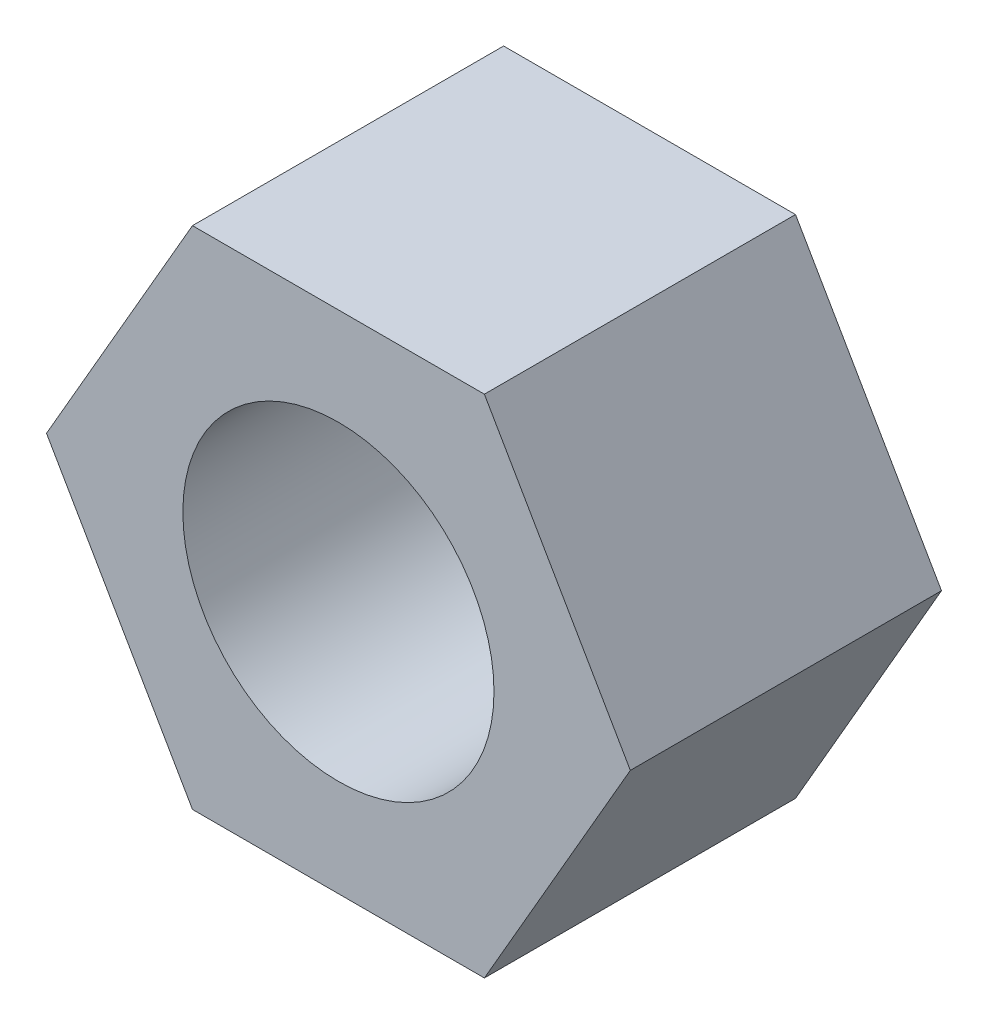
SolidWorks part; units mm, degrees
ref_plane "Front" through (0, 0, 0) normal (0, 0, 1) x (1, 0, 0)
ref_plane "Top" through (0, 0, 0) normal (0, 1, 0) x (1, 0, 0)
ref_plane "Right" through (0, 0, 0) normal (1, 0, 0) x (0, 0, -1)
sketch "Эскиз1" plane through (0, 0, 0) normal (0, 0, 1) x (1, 0, 0)
  line L1 (-3.7528, 6.5) -> (-7.5056, 0)
  line L2 (-7.5056, 0) -> (-3.7528, -6.5)
  line L3 (-3.7528, -6.5) -> (3.7528, -6.5)
  line L4 (3.7528, -6.5) -> (7.5056, 0)
  line L5 (7.5056, 0) -> (3.7528, 6.5)
  line L6 (3.7528, 6.5) -> (-3.7528, 6.5)
  circle A0 centre (0, 0) radius 6.5 construction
  circle A1 centre (0, 0) radius 4
  dimension "D1" = 8
  dimension "D2" = 13
extrude "Гайка_М4" add sketch "Эскиз1" along normal blind 8
